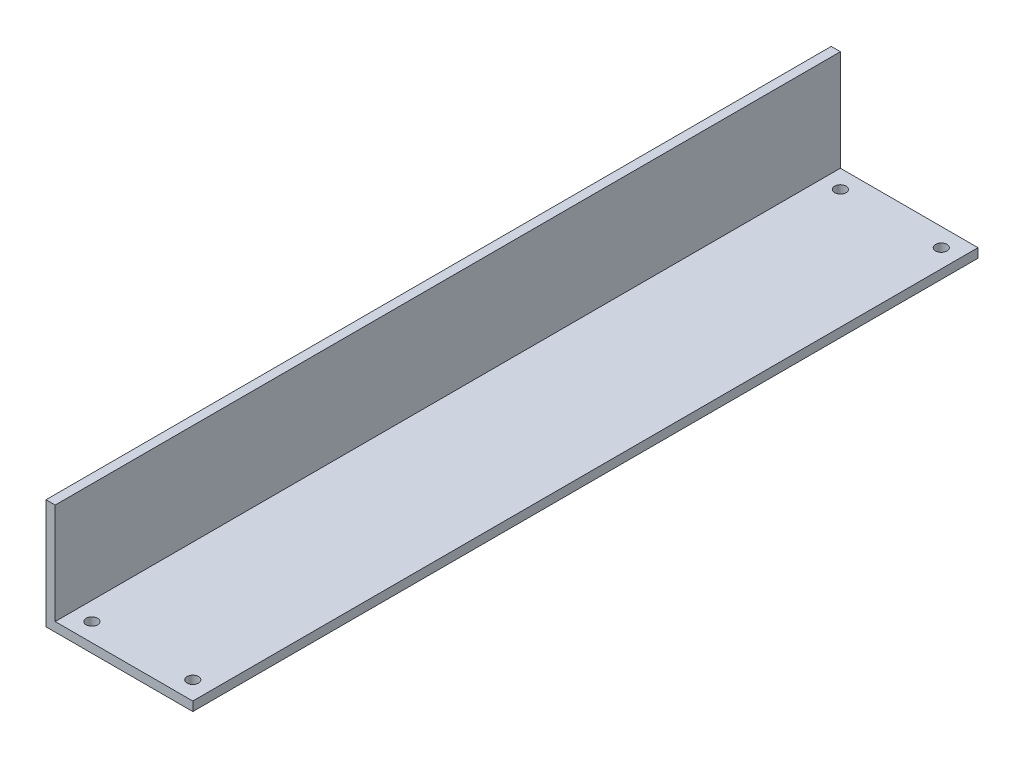
SolidWorks part; units mm, degrees
ref_plane "Front Plane" through (0, 0, 0) normal (0, 0, 1) x (1, 0, 0)
ref_plane "Top Plane" through (0, 0, 0) normal (0, 1, 0) x (1, 0, 0)
ref_plane "Right Plane" through (0, 0, 0) normal (1, 0, 0) x (0, 0, -1)
sketch "Sketch1" plane through (0, 0, 0) normal (0, 0, 1) x (1, 0, 0)
  line L0 (0, 0) -> (0, 101.6)
  line L1 (0, 0) -> (101.6, 0)
  line L2 (6.35, 6.35) -> (6.35, 101.6)
  line L3 (6.35, 6.35) -> (101.6, 6.35)
  line L4 (0, 101.6) -> (6.35, 101.6)
  line L5 (101.6, 6.35) -> (101.6, 0)
  line L6 (0, 76.2) -> (6.35, 76.2)
  dimension "D2" = 101.6
  dimension "D3" = 25.4
  dimension "D1" = 6.35
extrude "Boss-Extrude1" add sketch "Sketch1" along normal offset from surface (543.5 mm away) 12.7 contours L6 L0 L1 L5 L3 L2
sketch "Sketch4" plane through (0, 0, 0) normal (0, -1, 0) x (1, 0, 0)
  circle A0 centre (88.9, 530.8) radius 3.9688 construction
  circle A1 centre (88.9, 530.8) radius 3.9688
  circle A2 centre (19.05, 530.8) radius 3.9687 construction
  circle A3 centre (19.05, 530.8) radius 3.9687
  circle A4 centre (19.05, 12.7) radius 3.9688 construction
  circle A5 centre (19.05, 12.7) radius 3.9687
  circle A6 centre (88.9, 12.7) radius 3.9688 construction
  circle A7 centre (88.9, 12.7) radius 3.9688
extrude "Cut-Extrude1" cut sketch "Sketch4" against normal through all
